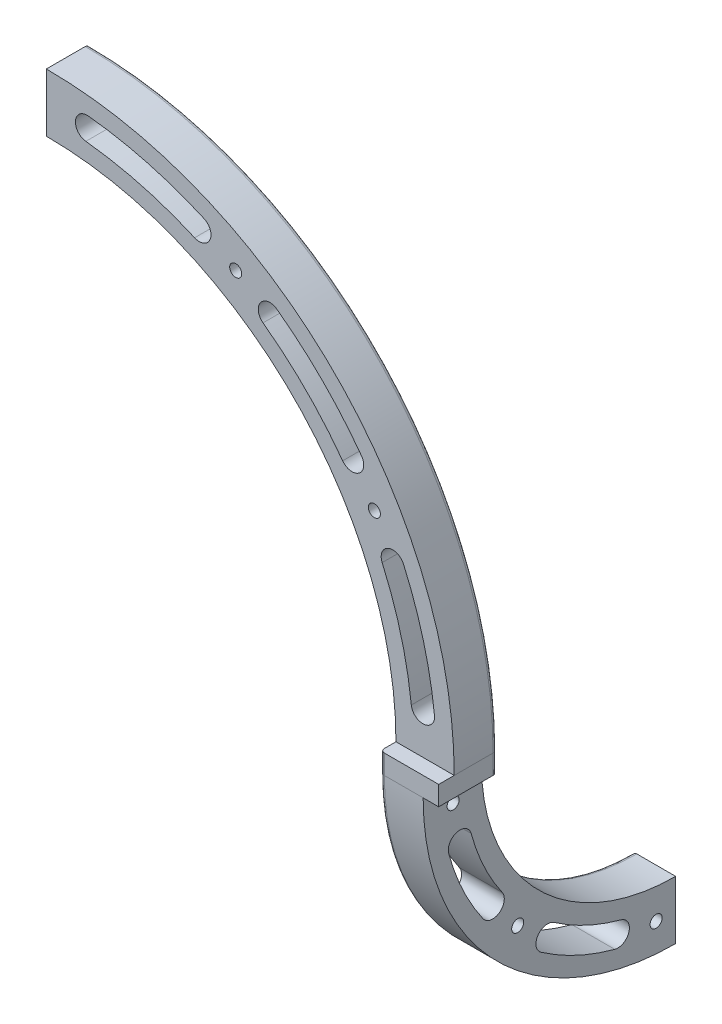
SolidWorks part; units mm, degrees
ref_plane "前视基准面" through (0, 0, 0) normal (0, 0, 1) x (1, 0, 0)
ref_plane "上视基准面" through (0, 0, 0) normal (0, 1, 0) x (1, 0, 0)
ref_plane "右视基准面" through (0, 0, 0) normal (1, 0, 0) x (0, 0, -1)
other "Configuration Table"
sketch "草图1" plane through (0, 0, 0) normal (0, 0, 1) x (1, 0, 0)
  line L0 (0, 105) -> (0, 0) construction
  line L1 (0, 0) -> (105, 0) construction
  line L2 (90, 0) -> (105, 0)
  line L3 (0, 105) -> (0, 90)
  arc A0 (0, 105) -> (105, 0) centre (0, 0) cw
  arc A1 (0, 90) -> (90, 0) centre (0, 0) cw
  dimension "D1" = 105
  dimension "D2" = 90
extrude "凸台-拉伸1" add sketch "草图1" along normal blind 15
sketch "草图2" plane through (0, 0, 0) normal (0, -1, 0) x (1, 0, 0)
  line L1 (90, 15) -> (105, 15)
  line L2 (90, 15) -> (90, 0)
  line L3 (90, 0) -> (105, 0)
  line L4 (105, 15) -> (105, 0)
extrude "凸台-拉伸2" add sketch "草图2" along normal blind 5
sketch "草图3" plane through (105, 0, 0) normal (1, 0, 0) x (0, 0, -1)
  line L0 (0, -5) -> (50, -5) construction
  line L1 (50, -5) -> (50, -55) construction
  line L2 (50, -55) -> (50, -70)
  line L3 (-15, -5) -> (0, -5)
  arc A0 (0, -5) -> (50, -55) centre (50, -5) ccw
  arc A1 (-15, -5) -> (50, -70) centre (50, -5) ccw
  dimension "D1" = 50
extrude "凸台-拉伸3" add sketch "草图3" against normal blind 15
sketch "草图4" plane through (0, 0, 15) normal (0, 0, 1) x (1, 0, 0)
  line L0 (25.2349, 94.1778) -> (0, 0) construction
  line L1 (0, 0) -> (68.9429, 68.9429) construction
  line L2 (0, 0) -> (94.1778, 25.2349) construction
  line L3 (0, 0) -> (90, 0) construction
  line L4 (48.75, 84.4375) -> (0, 0) construction
  line L5 (84.4375, 48.75) -> (0, 0) construction
  arc A0 (10.4903, 96.934) -> (39.3822, 89.1925) centre (0, 0) cw construction
  arc A1 (40.5939, 91.9368) -> (10.813, 99.9166) centre (0, 0) ccw
  arc A2 (38.1704, 86.4481) -> (10.1675, 93.9514) centre (0, 0) ccw
  arc A3 (38.1704, 86.4481) -> (40.5939, 91.9368) centre (39.3822, 89.1925) ccw
  arc A4 (10.813, 99.9166) -> (10.1675, 93.9514) centre (10.4903, 96.934) ccw
  arc A5 (57.5518, 78.7022) -> (78.7022, 57.5518) centre (0, 0) cw construction
  arc A6 (81.1238, 59.3227) -> (59.3227, 81.1238) centre (0, 0) ccw
  arc A7 (76.2806, 55.781) -> (55.781, 76.2806) centre (0, 0) ccw
  arc A8 (76.2806, 55.781) -> (81.1238, 59.3227) centre (78.7022, 57.5518) ccw
  arc A9 (59.3227, 81.1238) -> (55.781, 76.2806) centre (57.5518, 78.7022) ccw
  arc A10 (89.1925, 39.3822) -> (96.934, 10.4903) centre (0, 0) cw construction
  arc A11 (99.9166, 10.813) -> (91.9368, 40.5939) centre (0, 0) ccw
  arc A12 (93.9514, 10.1675) -> (86.4481, 38.1704) centre (0, 0) ccw
  arc A13 (93.9514, 10.1675) -> (99.9166, 10.813) centre (96.934, 10.4903) ccw
  arc A14 (91.9368, 40.5939) -> (86.4481, 38.1704) centre (89.1925, 39.3822) ccw
  circle A17 centre (84.4375, 48.75) radius 1.55
  circle A18 centre (48.75, 84.4375) radius 1.55
  point P4 (25.2349, 94.1778)
  point P9 (68.9429, 68.9429)
  point P18 (94.1778, 25.2349)
  dimension "D1" = 3
  dimension "D2" = 3
  dimension "D3" = 3
  dimension "D7" = 97.5
  dimension "D8" = 97.5
  dimension "D9" = 97.5
  dimension "D12" = 3.1
  dimension "D13" = 3.1
  dimension "D14" = 15
  dimension "D4" = 15
  dimension "D5" = 45
  dimension "D6" = 75
  dimension "D10" = 97.5
  dimension "D11" = 97.5
  dimension "D15" = 15
  dimension "D16" = 15
  dimension "D17" = 15
  dimension "D18" = 15
sketch "草图5" plane through (105, 0, 0) normal (1, 0, 0) x (0, 0, -1)
  line L0 (-2.1127, -29.3006) -> (50, -5) construction
  line L1 (50, -5) -> (25.6994, -57.1127) construction
  line L2 (50, -55) -> (50, -5) construction
  line L3 (50, -5) -> (0, -5) construction
  line L4 (-7.2812, -10.0115) -> (50, -5) construction
  line L5 (50, -5) -> (9.3414, -45.6586) construction
  line L6 (50, -5) -> (44.9694, -62.5) construction
  arc A0 (-5.5348, -19.9043) -> (2.8856, -37.9618) centre (50, -5) ccw construction
  arc A1 (-8.4322, -20.6819) -> (0.4274, -39.6816) centre (50, -5) ccw
  arc A2 (-2.6373, -19.1267) -> (5.3437, -36.2421) centre (50, -5) ccw
  arc A3 (-2.6373, -19.1267) -> (-8.4322, -20.6819) centre (-5.5348, -19.9043) ccw
  arc A4 (0.4274, -39.6816) -> (5.3437, -36.2421) centre (2.8856, -37.9618) ccw
  arc A5 (17.0382, -52.1144) -> (35.0957, -60.5348) centre (50, -5) ccw construction
  arc A6 (15.3184, -54.5726) -> (34.3181, -63.4322) centre (50, -5) ccw
  arc A7 (18.7579, -49.6563) -> (35.8733, -57.6373) centre (50, -5) ccw
  arc A8 (18.7579, -49.6563) -> (15.3184, -54.5726) centre (17.0382, -52.1144) ccw
  arc A9 (34.3181, -63.4322) -> (35.8733, -57.6373) centre (35.0957, -60.5348) ccw
  circle A13 centre (44.9694, -62.5) radius 1.55
  circle A14 centre (9.3414, -45.6586) radius 1.55
  circle A15 centre (-7.2812, -10.0115) radius 1.55
  point P4 (-2.1127, -29.3006)
  point P9 (25.6994, -57.1127)
  point P28 (27.1678, -57.7725)
  point P31 (-2.4634, -28.5339)
  dimension "D1" = 57.5
  dimension "D2" = 57.5
  dimension "D8" = 3.1
  dimension "D9" = 3.1
  dimension "D10" = 3.1
  dimension "D12" = 25
  dimension "D13" = 3
  dimension "D16" = 3
  dimension "D3" = 57.5
  dimension "D4" = 57.5
  dimension "D5" = 57.5
  dimension "D6" = 10
  dimension "D7" = 10
  dimension "D11" = 45
  dimension "D14" = 5
  dimension "D15" = 5
  dimension "D17" = 25
extrude "切除-拉伸1" cut sketch "草图4" against normal through all
extrude "切除-拉伸2" cut sketch "草图5" against normal through all
sketch "草图6" plane through (105, 0, 0) normal (1, 0, 0) x (0, 0, -1)
  line L0 (50, -55) -> (50, -70)
  line L1 (0, -5) -> (-15, -5)
  arc A0 (0, -5) -> (50, -55) centre (50, -5) ccw
  arc A1 (-15, -5) -> (50, -70) centre (50, -5) ccw
extrude "切除-拉伸3" cut sketch "草图6" against normal blind 4
sketch "草图7" plane through (0, 0, 15) normal (0, 0, 1) x (1, 0, 0)
  line L0 (0, 105) -> (0, 90)
  line L1 (90, 0) -> (105, 0)
  line L2 (90, -5) -> (90, 0) construction
  arc A0 (0, 90) -> (90, 0) centre (0, 0) cw
  arc A1 (0, 105) -> (105, 0) centre (0, 0) cw
extrude "切除-拉伸4" cut sketch "草图7" against normal blind 4
fillet "圆角1" radius 1 7 edges at (90, -2.5, 15) (90, -40.3553, -14.6447) (90, -2.5, 0) (105, -2.5, 0) (90, -50.9619, -4.0381) (63.6396, 63.6396, 0) (74.2462, 74.2462, 0)
